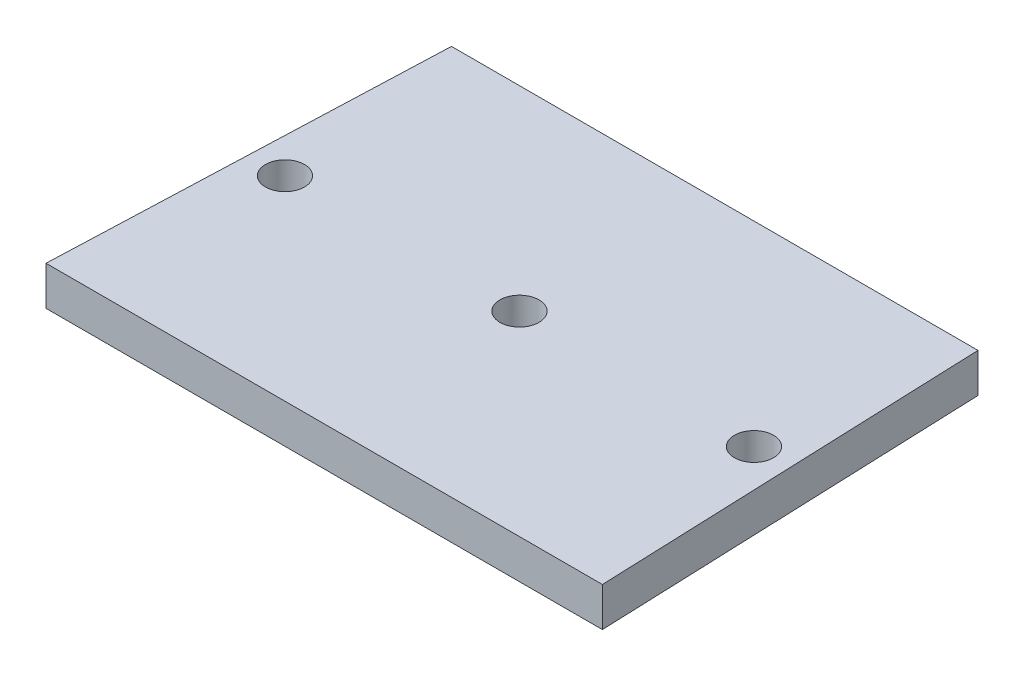
SolidWorks part; units mm, degrees
ref_plane "Alzado" through (0, 0, 0) normal (0, 0, 1) x (1, 0, 0)
ref_plane "Planta" through (0, 0, 0) normal (0, 1, 0) x (1, 0, 0)
ref_plane "Vista lateral" through (0, 0, 0) normal (1, 0, 0) x (0, 0, -1)
sketch "Croquis1" plane through (0, 0, 0) normal (0, 1, 0) x (1, 0, 0)
  line L0 (31, -188.7738) -> (-31, -188.7738)
  line L1 (-31, -188.7738) -> (-16.5545, 188.7738)
  line L2 (-16.5545, 188.7738) -> (16.5545, 188.7738)
  line L3 (0, -188.7738) -> (0, -170.865) construction
  line L4 (31, -188.7738) -> (16.5545, 188.7738)
  point P3 (0, -188.7738)
  point P7 (0, 188.7738)
  dimension "D1" = 62
extrude "Saliente-Extruir1" add sketch "Croquis1" along normal blind 3
sketch "Croquis2" plane through (0, 3, 0) normal (0, 1, 0) x (1, 0, 0)
  circle A3 centre (0, 78.2977) radius 1.5
  circle A4 centre (-18, 78.2977) radius 1.5
  circle A5 centre (18, 78.2977) radius 1.5
  point P6 (0, 78.2977)
extrude "Cortar-Extruir1" cut sketch "Croquis2" against normal blind 4
sketch "Croquis3" plane through (0, 3, 0) normal (0, 1, 0) x (1, 0, 0)
  line L3 (31, -188.7738) -> (16.5545, 188.7738) construction
  line L7 (-20.208, 190.9046) -> (20.208, 190.9046)
  line L8 (-20.208, 190.9046) -> (-20.208, 93.2867)
  line L9 (-20.208, 93.2867) -> (20.208, 93.2867)
  line L10 (20.208, 190.9046) -> (20.208, 93.2867)
  line L11 (-31, -188.7738) -> (31.5929, -188.7738)
  line L12 (-31, -188.7738) -> (-31, 63.3086)
  line L13 (-31, 63.3086) -> (31.5929, 63.3086)
  line L14 (31.5929, -188.7738) -> (31.5929, 63.3086)
  point P5 (-20.7815, 78.2977)
extrude "Cortar-Extruir2" cut sketch "Croquis3" against normal blind 18
